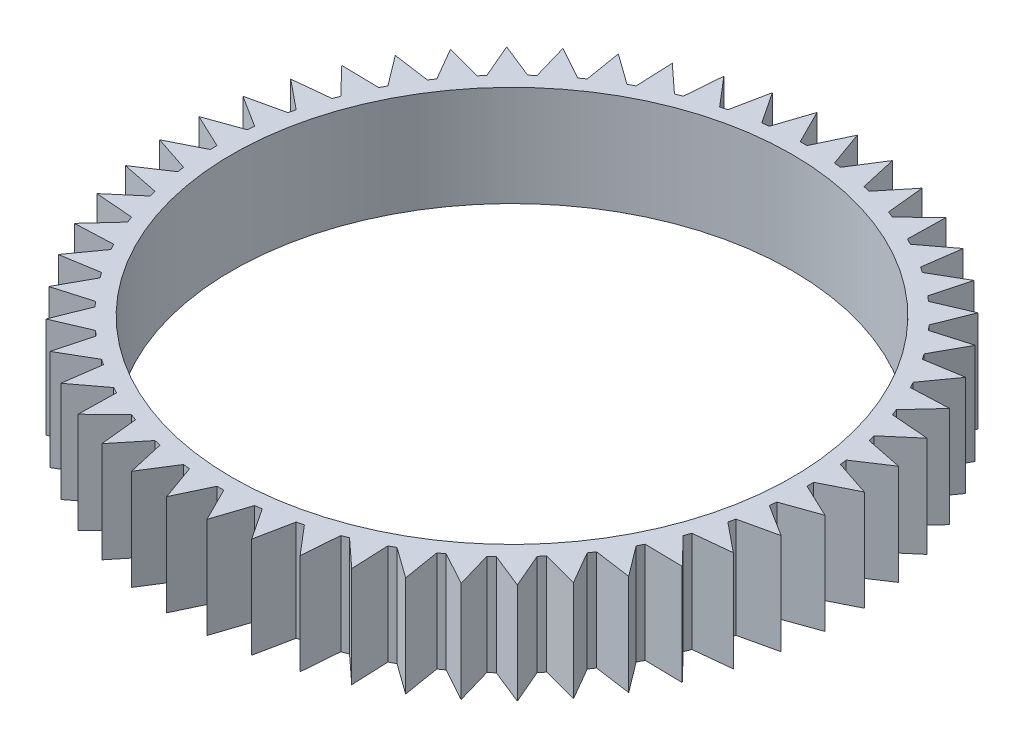
SolidWorks part; units mm, degrees
ref_plane "Front Plane" through (0, 0, 0) normal (0, 0, 1) x (1, 0, 0)
ref_plane "Top Plane" through (0, 0, 0) normal (0, 1, 0) x (1, 0, 0)
ref_plane "Right Plane" through (0, 0, 0) normal (1, 0, 0) x (0, 0, -1)
sketch "Sketch1" plane through (0, 0, 0) normal (0, 1, 0) x (1, 0, 0)
  line L0 (0, 23.45) -> (1.2824, 26.1621)
  line L1 (1.2824, 26.1621) -> (2.2933, 23.3376)
  line L2 (2.8266, 23.279) -> (4.4265, 25.8168)
  line L3 (4.4265, 25.8168) -> (5.0897, 22.891)
  line L4 (5.612, 22.7686) -> (7.5061, 25.095)
  line L5 (7.5061, 25.095) -> (7.8118, 22.1106)
  line L6 (8.3155, 21.9261) -> (10.4762, 24.0073)
  line L7 (10.4762, 24.0073) -> (10.4199, 21.0078)
  line L8 (10.8978, 20.7639) -> (13.2936, 22.5695)
  line L9 (13.2936, 22.5695) -> (12.8762, 19.5986)
  line L10 (13.3211, 19.299) -> (15.9171, 20.8025)
  line L11 (15.9171, 20.8025) -> (15.1446, 17.9037)
  line L12 (15.5502, 17.5526) -> (18.3086, 18.7323)
  line L13 (18.3086, 18.7323) -> (17.1923, 15.9477)
  line L14 (17.5526, 15.5502) -> (20.433, 16.3888)
  line L15 (20.433, 16.3888) -> (18.9892, 13.7591)
  line L16 (19.299, 13.3211) -> (22.2595, 13.8064)
  line L17 (22.2595, 13.8064) -> (20.5092, 11.3699)
  line L18 (20.7639, 10.8978) -> (23.7613, 11.0227)
  line L19 (23.7613, 11.0227) -> (21.7302, 8.8149)
  line L20 (21.9261, 8.3155) -> (24.9167, 8.0782)
  line L21 (24.9167, 8.0782) -> (22.6343, 6.1313)
  line L22 (22.7686, 5.612) -> (25.7088, 5.0159)
  line L23 (25.7088, 5.0159) -> (23.2083, 3.3583)
  line L24 (23.279, 2.8266) -> (26.1259, 1.8805)
  line L25 (26.1259, 1.8805) -> (23.4439, 0.5364)
  line L26 (23.45, 0) -> (26.1621, -1.2824)
  line L27 (26.1621, -1.2824) -> (23.3376, -2.2933)
  line L28 (23.279, -2.8266) -> (25.8168, -4.4265)
  line L29 (25.8168, -4.4265) -> (22.891, -5.0897)
  line L30 (22.7686, -5.612) -> (25.095, -7.5061)
  line L31 (25.095, -7.5061) -> (22.1106, -7.8118)
  line L32 (21.9261, -8.3155) -> (24.0073, -10.4762)
  line L33 (24.0073, -10.4762) -> (21.0078, -10.4199)
  line L34 (20.7639, -10.8978) -> (22.5695, -13.2936)
  line L35 (22.5695, -13.2936) -> (19.5986, -12.8762)
  line L36 (19.299, -13.3211) -> (20.8025, -15.9171)
  line L37 (20.8025, -15.9171) -> (17.9037, -15.1446)
  line L38 (17.5526, -15.5502) -> (18.7323, -18.3086)
  line L39 (18.7323, -18.3086) -> (15.9477, -17.1923)
  line L40 (15.5502, -17.5526) -> (16.3888, -20.433)
  line L41 (16.3888, -20.433) -> (13.7591, -18.9892)
  line L42 (13.3211, -19.299) -> (13.8064, -22.2595)
  line L43 (13.8064, -22.2595) -> (11.3699, -20.5092)
  line L44 (10.8978, -20.7639) -> (11.0227, -23.7613)
  line L45 (11.0227, -23.7613) -> (8.8149, -21.7302)
  line L46 (8.3155, -21.9261) -> (8.0782, -24.9167)
  line L47 (8.0782, -24.9167) -> (6.1313, -22.6343)
  line L48 (5.612, -22.7686) -> (5.0159, -25.7088)
  line L49 (5.0159, -25.7088) -> (3.3583, -23.2083)
  line L50 (2.8266, -23.279) -> (1.8805, -26.1259)
  line L51 (1.8805, -26.1259) -> (0.5364, -23.4439)
  line L52 (0, -23.45) -> (-1.2824, -26.1621)
  line L53 (-1.2824, -26.1621) -> (-2.2933, -23.3376)
  line L54 (-2.8266, -23.279) -> (-4.4265, -25.8168)
  line L55 (-4.4265, -25.8168) -> (-5.0897, -22.891)
  line L56 (-5.612, -22.7686) -> (-7.5061, -25.095)
  line L57 (-7.5061, -25.095) -> (-7.8118, -22.1106)
  line L58 (-8.3155, -21.9261) -> (-10.4762, -24.0073)
  line L59 (-10.4762, -24.0073) -> (-10.4199, -21.0078)
  line L60 (-10.8978, -20.7639) -> (-13.2936, -22.5695)
  line L61 (-13.2936, -22.5695) -> (-12.8762, -19.5986)
  line L62 (-13.3211, -19.299) -> (-15.9171, -20.8025)
  line L63 (-15.9171, -20.8025) -> (-15.1446, -17.9037)
  line L64 (-15.5502, -17.5526) -> (-18.3086, -18.7323)
  line L65 (-18.3086, -18.7323) -> (-17.1923, -15.9477)
  line L66 (-17.5526, -15.5502) -> (-20.433, -16.3888)
  line L67 (-20.433, -16.3888) -> (-18.9892, -13.7591)
  line L68 (-19.299, -13.3211) -> (-22.2595, -13.8064)
  line L69 (-22.2595, -13.8064) -> (-20.5092, -11.3699)
  line L70 (-20.7639, -10.8978) -> (-23.7613, -11.0227)
  line L71 (-23.7613, -11.0227) -> (-21.7302, -8.8149)
  line L72 (-21.9261, -8.3155) -> (-24.9167, -8.0782)
  line L73 (-24.9167, -8.0782) -> (-22.6343, -6.1313)
  line L74 (-22.7686, -5.612) -> (-25.7088, -5.0159)
  line L75 (-25.7088, -5.0159) -> (-23.2083, -3.3583)
  line L76 (-23.279, -2.8266) -> (-26.1259, -1.8805)
  line L77 (-26.1259, -1.8805) -> (-23.4439, -0.5364)
  line L78 (-23.45, 0) -> (-26.1621, 1.2824)
  line L79 (-26.1621, 1.2824) -> (-23.3376, 2.2933)
  line L80 (-23.279, 2.8266) -> (-25.8168, 4.4265)
  line L81 (-25.8168, 4.4265) -> (-22.891, 5.0897)
  line L82 (-22.7686, 5.612) -> (-25.095, 7.5061)
  line L83 (-25.095, 7.5061) -> (-22.1106, 7.8118)
  line L84 (-21.9261, 8.3155) -> (-24.0073, 10.4762)
  line L85 (-24.0073, 10.4762) -> (-21.0078, 10.4199)
  line L86 (-20.7639, 10.8978) -> (-22.5695, 13.2936)
  line L87 (-22.5695, 13.2936) -> (-19.5986, 12.8762)
  line L88 (-19.299, 13.3211) -> (-20.8025, 15.9171)
  line L89 (-20.8025, 15.9171) -> (-17.9037, 15.1446)
  line L90 (-17.5526, 15.5502) -> (-18.7323, 18.3086)
  line L91 (-18.7323, 18.3086) -> (-15.9477, 17.1923)
  line L92 (-15.5502, 17.5526) -> (-16.3888, 20.433)
  line L93 (-16.3888, 20.433) -> (-13.7591, 18.9892)
  line L94 (-13.3211, 19.299) -> (-13.8064, 22.2595)
  line L95 (-13.8064, 22.2595) -> (-11.3699, 20.5092)
  line L96 (-10.8978, 20.7639) -> (-11.0227, 23.7613)
  line L97 (-11.0227, 23.7613) -> (-8.8149, 21.7302)
  line L98 (-8.3155, 21.9261) -> (-8.0782, 24.9167)
  line L99 (-8.0782, 24.9167) -> (-6.1313, 22.6343)
  line L100 (-5.612, 22.7686) -> (-5.0159, 25.7088)
  line L101 (-5.0159, 25.7088) -> (-3.3583, 23.2083)
  line L102 (-2.8266, 23.279) -> (-1.8805, 26.1259)
  line L103 (-1.8805, 26.1259) -> (-0.5364, 23.4439)
  circle A0 centre (0, 0) radius 22.25
  circle A1 centre (0, 0) radius 23.45 construction
  arc A2 (2.2933, 23.3376) -> (2.8266, 23.279) centre (0, 0) cw
  arc A3 (5.0897, 22.891) -> (5.612, 22.7686) centre (0, 0) cw
  arc A4 (7.8118, 22.1106) -> (8.3155, 21.9261) centre (0, 0) cw
  arc A5 (10.4199, 21.0078) -> (10.8978, 20.7639) centre (0, 0) cw
  arc A6 (12.8762, 19.5986) -> (13.3211, 19.299) centre (0, 0) cw
  arc A7 (15.1446, 17.9037) -> (15.5502, 17.5526) centre (0, 0) cw
  arc A8 (17.1923, 15.9477) -> (17.5526, 15.5502) centre (0, 0) cw
  arc A9 (18.9892, 13.7591) -> (19.299, 13.3211) centre (0, 0) cw
  arc A10 (20.5092, 11.3699) -> (20.7639, 10.8978) centre (0, 0) cw
  arc A11 (21.7302, 8.8149) -> (21.9261, 8.3155) centre (0, 0) cw
  arc A12 (22.6343, 6.1313) -> (22.7686, 5.612) centre (0, 0) cw
  arc A13 (23.2083, 3.3583) -> (23.279, 2.8266) centre (0, 0) cw
  arc A14 (23.4439, 0.5364) -> (23.45, 0) centre (0, 0) cw
  arc A15 (23.3376, -2.2933) -> (23.279, -2.8266) centre (0, 0) cw
  arc A16 (22.891, -5.0897) -> (22.7686, -5.612) centre (0, 0) cw
  arc A17 (22.1106, -7.8118) -> (21.9261, -8.3155) centre (0, 0) cw
  arc A18 (21.0078, -10.4199) -> (20.7639, -10.8978) centre (0, 0) cw
  arc A19 (19.5986, -12.8762) -> (19.299, -13.3211) centre (0, 0) cw
  arc A20 (17.9037, -15.1446) -> (17.5526, -15.5502) centre (0, 0) cw
  arc A21 (15.9477, -17.1923) -> (15.5502, -17.5526) centre (0, 0) cw
  arc A22 (13.7591, -18.9892) -> (13.3211, -19.299) centre (0, 0) cw
  arc A23 (11.3699, -20.5092) -> (10.8978, -20.7639) centre (0, 0) cw
  arc A24 (8.8149, -21.7302) -> (8.3155, -21.9261) centre (0, 0) cw
  arc A25 (6.1313, -22.6343) -> (5.612, -22.7686) centre (0, 0) cw
  arc A26 (3.3583, -23.2083) -> (2.8266, -23.279) centre (0, 0) cw
  arc A27 (0.5364, -23.4439) -> (0, -23.45) centre (0, 0) cw
  arc A28 (-2.2933, -23.3376) -> (-2.8266, -23.279) centre (0, 0) cw
  arc A29 (-5.0897, -22.891) -> (-5.612, -22.7686) centre (0, 0) cw
  arc A30 (-7.8118, -22.1106) -> (-8.3155, -21.9261) centre (0, 0) cw
  arc A31 (-10.4199, -21.0078) -> (-10.8978, -20.7639) centre (0, 0) cw
  arc A32 (-12.8762, -19.5986) -> (-13.3211, -19.299) centre (0, 0) cw
  arc A33 (-15.1446, -17.9037) -> (-15.5502, -17.5526) centre (0, 0) cw
  arc A34 (-17.1923, -15.9477) -> (-17.5526, -15.5502) centre (0, 0) cw
  arc A35 (-18.9892, -13.7591) -> (-19.299, -13.3211) centre (0, 0) cw
  arc A36 (-20.5092, -11.3699) -> (-20.7639, -10.8978) centre (0, 0) cw
  arc A37 (-21.7302, -8.8149) -> (-21.9261, -8.3155) centre (0, 0) cw
  arc A38 (-22.6343, -6.1313) -> (-22.7686, -5.612) centre (0, 0) cw
  arc A39 (-23.2083, -3.3583) -> (-23.279, -2.8266) centre (0, 0) cw
  arc A40 (-23.4439, -0.5364) -> (-23.45, 0) centre (0, 0) cw
  arc A41 (-23.3376, 2.2933) -> (-23.279, 2.8266) centre (0, 0) cw
  arc A42 (-22.891, 5.0897) -> (-22.7686, 5.612) centre (0, 0) cw
  arc A43 (-22.1106, 7.8118) -> (-21.9261, 8.3155) centre (0, 0) cw
  arc A44 (-21.0078, 10.4199) -> (-20.7639, 10.8978) centre (0, 0) cw
  arc A45 (-19.5986, 12.8762) -> (-19.299, 13.3211) centre (0, 0) cw
  arc A46 (-17.9037, 15.1446) -> (-17.5526, 15.5502) centre (0, 0) cw
  arc A47 (-15.9477, 17.1923) -> (-15.5502, 17.5526) centre (0, 0) cw
  arc A48 (-13.7591, 18.9892) -> (-13.3211, 19.299) centre (0, 0) cw
  arc A49 (-11.3699, 20.5092) -> (-10.8978, 20.7639) centre (0, 0) cw
  arc A50 (-8.8149, 21.7302) -> (-8.3155, 21.9261) centre (0, 0) cw
  arc A51 (-6.1313, 22.6343) -> (-5.612, 22.7686) centre (0, 0) cw
  arc A52 (-3.3583, 23.2083) -> (-2.8266, 23.279) centre (0, 0) cw
  arc A53 (-0.5364, 23.4439) -> (0, 23.45) centre (0, 0) cw
  point P163 (0, 0)
  point P268 (0, 0)
  dimension "D1" = 44.5
  dimension "D3" = 3
  dimension "D4" = 315
  dimension "D2" = 1.2
  dimension "D5" = 52
  dimension "D6" = 52
extrude "Boss-Extrude1" add sketch "Sketch1" along normal blind 8
